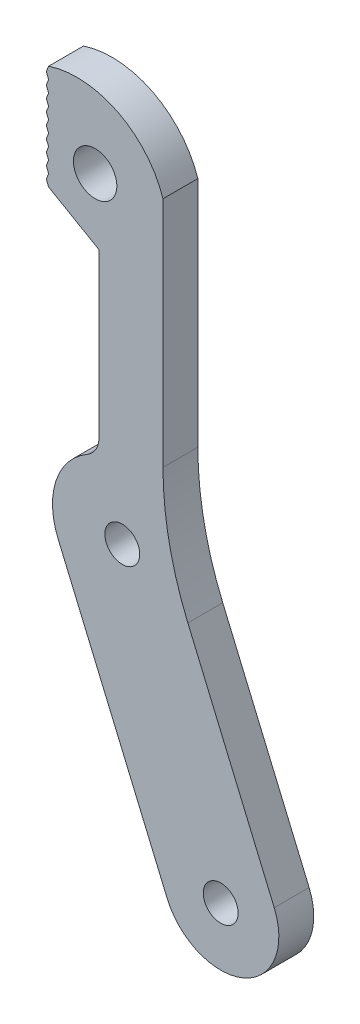
SolidWorks part; units mm, degrees
ref_plane "Front Plane" through (0, 0, 0) normal (0, 0, 1) x (1, 0, 0)
ref_plane "Top Plane" through (0, 0, 0) normal (0, 1, 0) x (1, 0, 0)
ref_plane "Right Plane" through (0, 0, 0) normal (1, 0, 0) x (0, 0, -1)
sketch "Sketch1" plane through (0, 0, 0) normal (0, 0, 1) x (1, 0, 0)
  line L0 (19.9553, -21.6867) -> (19.9553, -7.6867)
  line L1 (19.9553, -7.6867) -> (15.6252, -5.1867)
  line L2 (15.4252, -4.6867) -> (15.6252, -5.1867)
  line L3 (15.4252, -4.6867) -> (15.6252, -4.1867)
  line L4 (16.4357, -30.9581) -> (25.8159, -53.0491)
  line L5 (35.0205, -49.1407) -> (27.5945, -31.652)
  line L6 (25.4553, -21.1407) -> (25.4553, -1.1407)
  line L8 (15.4252, -3.6867) -> (15.6252, -4.1867)
  line L9 (15.4252, -3.6867) -> (15.6252, -3.1867)
  line L10 (15.4252, -2.6867) -> (15.6252, -3.1867)
  line L11 (15.4252, -2.6867) -> (15.6252, -2.1867)
  line L12 (15.4252, -1.6867) -> (15.6252, -2.1867)
  line L13 (15.4252, -1.6867) -> (15.6252, -1.1867)
  line L14 (15.4252, -0.6867) -> (15.6252, -1.1867)
  line L15 (15.4252, -0.6867) -> (15.6252, -0.1867)
  line L16 (15.4252, 0.3133) -> (15.6252, -0.1867)
  line L17 (15.4252, 0.3133) -> (15.6252, 0.8133)
  line L18 (15.4252, 1.3133) -> (15.6252, 0.8133)
  line L19 (15.4252, 1.3133) -> (15.6252, 1.8133)
  line L20 (15.4252, 2.3133) -> (15.6252, 1.8133)
  line L21 (15.4252, 2.3133) -> (15.6252, 2.8133)
  line L22 (15.4252, 3.3133) -> (15.6252, 2.8133)
  line L23 (15.4252, 3.3133) -> (15.6252, 3.8133)
  arc A0 (19.9553, -21.6867) -> (18.9561, -23.4182) centre (17.9553, -21.6867) cw
  arc A1 (18.9561, -23.4182) -> (16.4357, -30.9581) centre (21.9585, -28.613) ccw
  arc A2 (25.8159, -53.0491) -> (35.0205, -49.1407) centre (30.4182, -51.0949) ccw
  arc A3 (27.5945, -31.652) -> (25.4553, -21.1407) centre (52.3494, -21.1407) cw
  arc A4 (15.6252, 3.8133) -> (25.4553, -1.1407) centre (18.0632, -3.5787) cw
  circle A5 centre (30.4182, -51.0949) radius 1.5
  circle A6 centre (19.6252, -2.1867) radius 1.8668
  circle A7 centre (21.9585, -28.613) radius 1.5
  dimension "D1" = 14
  dimension "D3" = 2
  dimension "D4" = 6
  dimension "D6" = 24
  dimension "D8" = 48
  dimension "D10" = 26.8941
  dimension "D14" = 1
  dimension "D16" = 3
  dimension "D17" = 4
  dimension "D18" = 3
  dimension "D2" = 5.5
  dimension "D5" = 10
  dimension "D7" = 20
  dimension "D9" = 19
  dimension "D11" = 5
  dimension "D12" = 0.5385
  dimension "D13" = 120
  dimension "D15" = 9
extrude "Boss-Extrude2" add sketch "Sketch1" along normal blind 3
